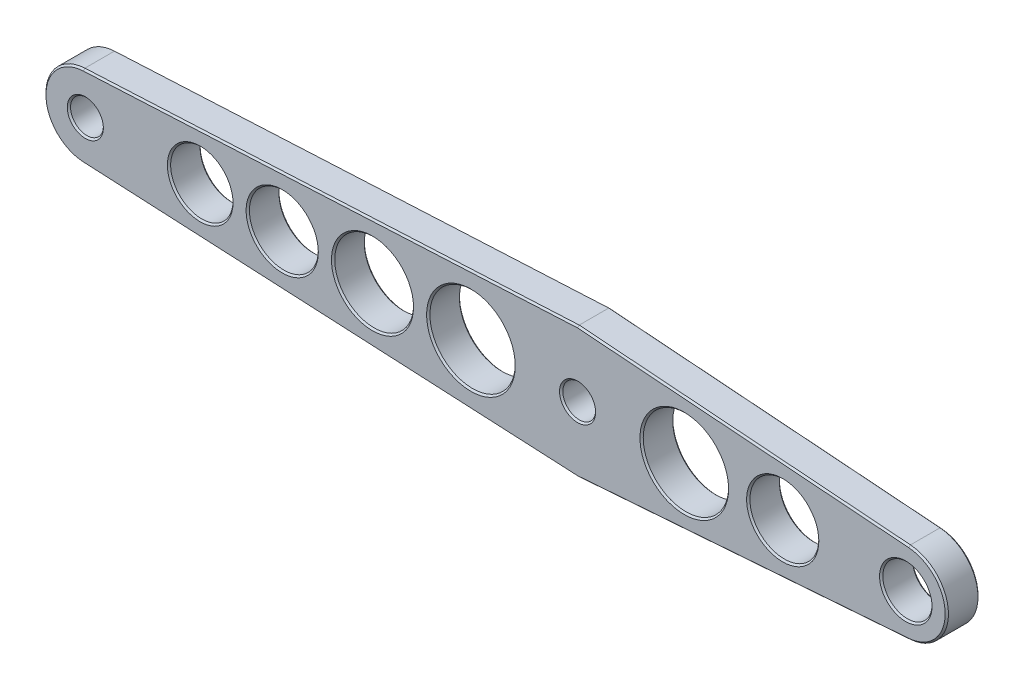
SolidWorks part; units mm, degrees
ref_plane "Front Plane" through (0, 0, 0) normal (0, 0, 1) x (1, 0, 0)
ref_plane "Top Plane" through (0, 0, 0) normal (0, 1, 0) x (1, 0, 0)
ref_plane "Right Plane" through (0, 0, 0) normal (1, 0, 0) x (0, 0, -1)
sketch "Sketch1" plane through (0, 0, 0) normal (0, 0, 1) x (1, 0, 0)
  line L0 (-30, 0) -> (20, 0) construction
  line L1 (0, 4) -> (0, -4) construction
  line L2 (-30.1246, 2.4969) -> (0, 4)
  line L3 (0, 4) -> (20.1861, 2.4931)
  line L4 (20.1861, -2.4931) -> (0, -4)
  line L5 (0, -4) -> (-30.1246, -2.4969)
  circle A0 centre (-30, 0) radius 1
  arc A1 (-30.1246, 2.4969) -> (-30.1246, -2.4969) centre (-30, 0) ccw
  circle A2 centre (-23, 0) radius 1.9
  circle A3 centre (-18, 0) radius 2.1
  circle A4 centre (-12.5, 0) radius 2.4
  circle A5 centre (0, 0) radius 1
  circle A6 centre (20, 0) radius 1.5
  arc A7 (20.1861, -2.4931) -> (20.1861, 2.4931) centre (20, 0) ccw
  circle A8 centre (-6.5, 0) radius 2.6
  circle A9 centre (6.5, 0) radius 2.6
  circle A10 centre (12.5, 0) radius 2.1
  point P26 (0, 0)
  point P28 (0, 0)
  dimension "D1" = 2
  dimension "D2" = 5
  dimension "D3" = 3.8
  dimension "D4" = 4.2
  dimension "D5" = 4.8
  dimension "D6" = 5.2
  dimension "D7" = 2
  dimension "D9" = 5
  dimension "D10" = 5.5
  dimension "D11" = 6
  dimension "D12" = 4.2
  dimension "D13" = 5.2
  dimension "D14" = 3
  dimension "D15" = 5
  dimension "D8" = 7
  dimension "D16" = 7.5
  dimension "D17" = 6
  dimension "D18" = 30
  dimension "D19" = 20
  dimension "D20" = 4
  dimension "D21" = 4
extrude "Boss-Extrude1" add sketch "Sketch1" along normal blind 2
chamfer "Chamfer1" distance 0.1 angle 45 30 edges at (9.1, 0, 0) (14.6, 0, 0) (-3.9, 0, 0) (21.5, 0, 0) (1, 0, 0) (-10.1, 0, 0) (-15.9, 0, 0) (-21.1, 0, 0) (-29, 0, 0) (-15.0623, -3.2484, 0) (10.0931, -3.2465, 0) (22.5, 0, 0) (10.0931, 3.2465, 0) (-15.0623, 3.2484, 0) (-32.5, 0, 0) (9.1, 0, 2) (-3.9, 0, 2) (1, 0, 2) (-15.9, 0, 2) (-29, 0, 2) (-15.0623, 3.2484, 2) (10.0931, 3.2465, 2) (22.5, 0, 2) (10.0931, -3.2465, 2) (-15.0623, -3.2484, 2) (-32.5, 0, 2) (-21.1, 0, 2) (-10.1, 0, 2) (21.5, 0, 2) (14.6, 0, 2)
